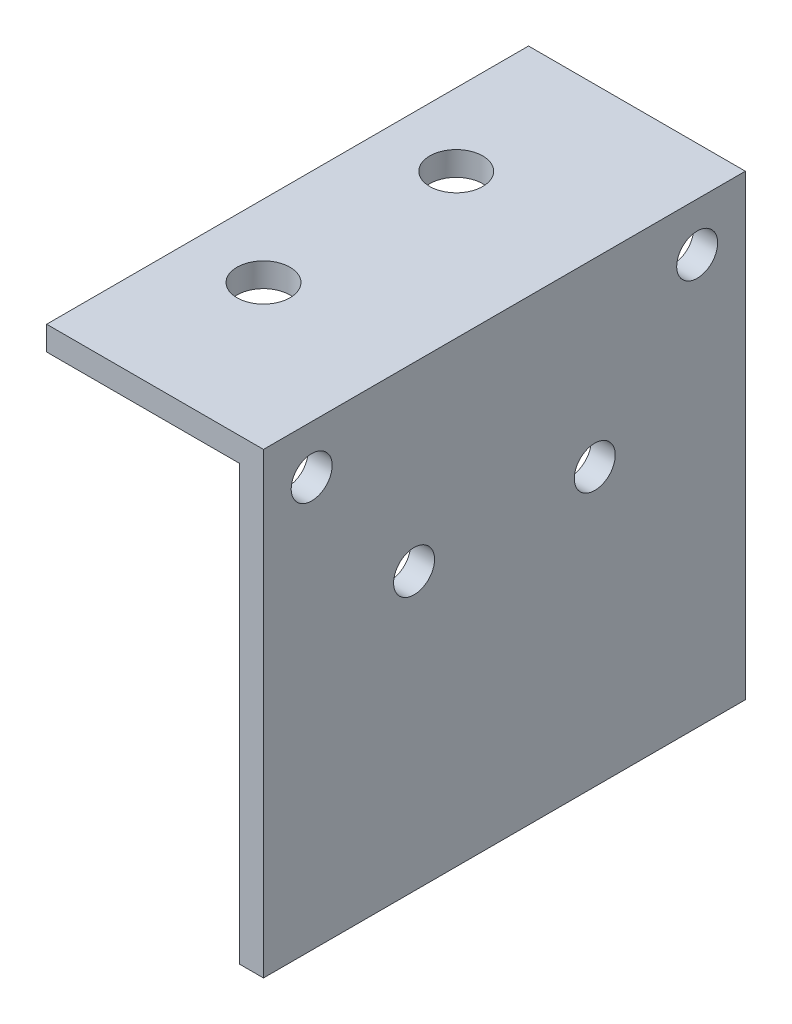
SolidWorks part; units mm, degrees
ref_plane "前视基准面" through (0, 0, 0) normal (0, 0, 1) x (1, 0, 0)
ref_plane "上视基准面" through (0, 0, 0) normal (0, 1, 0) x (1, 0, 0)
ref_plane "右视基准面" through (0, 0, 0) normal (1, 0, 0) x (0, 0, -1)
sketch "草图1" plane through (0, 0, 0) normal (0, 0, 1) x (1, 0, 0)
  line L0 (0, 0) -> (18, 0)
  line L1 (18, 0) -> (18, -38)
  line L2 (18, -38) -> (16, -38)
  line L3 (16, -38) -> (16, -2)
  line L4 (16, -2) -> (0, -2)
  line L5 (0, -2) -> (0, 0)
  dimension "D1" = 38
  dimension "D2" = 18
  dimension "D3" = 2
  dimension "D4" = 2
extrude "凸台-拉伸1" add sketch "草图1" along normal blind 40
sketch "草图2" plane through (0, 0, 0) normal (0, 1, 0) x (1, 0, 0)
  line L0 (0, -40) -> (0, 0) construction
  line L1 (18, -40) -> (0, -40) construction
  circle A0 centre (6, -28) radius 2.2
  circle A1 centre (6, -12) radius 2.2
  dimension "D1" = 4.4
  dimension "D2" = 4.4
  dimension "D3" = 16
  dimension "D4" = 12
  dimension "D5" = 6
extrude "切除-拉伸1" cut sketch "草图2" against normal up to next
sketch "草图3" plane through (18, 0, 0) normal (1, 0, 0) x (0, 0, -1)
  line L0 (-40, -38) -> (0, -38) construction
  line L1 (-40, -38) -> (-40, 0) construction
  line L2 (-40, 0) -> (0, 0) construction
  circle A0 centre (-27.5, -15) radius 1.7
  circle A1 centre (-12.5, -15) radius 1.7
  circle A2 centre (-36, -4) radius 1.7
  circle A3 centre (-4, -4) radius 1.7
  dimension "D1" = 3.4
  dimension "D2" = 3.4
  dimension "D6" = 3.4
  dimension "D7" = 3.4
  dimension "D3" = 15
  dimension "D4" = 23
  dimension "D5" = 12.5
  dimension "D8" = 32
  dimension "D9" = 4
  dimension "D10" = 4
extrude "切除-拉伸2" cut sketch "草图3" against normal up to next
